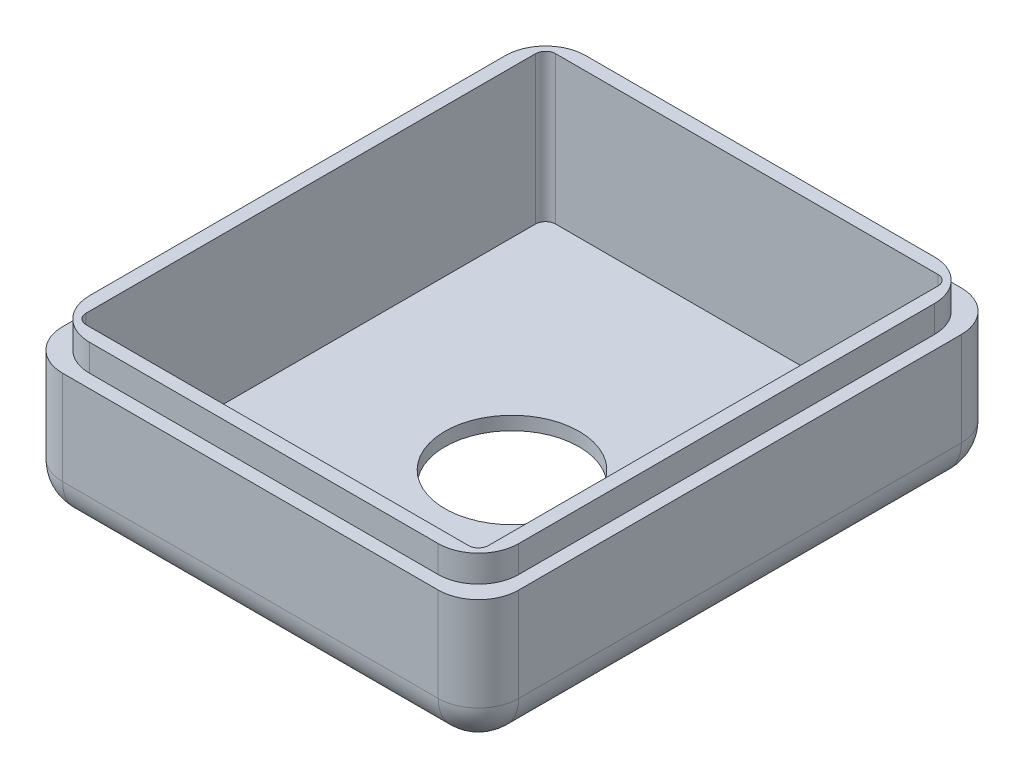
SolidWorks part; units mm, degrees
ref_plane "Piano frontale" through (0, 0, 0) normal (0, 0, 1) x (1, 0, 0)
ref_plane "Piano superiore" through (0, 0, 0) normal (0, 1, 0) x (1, 0, 0)
ref_plane "Piano destro" through (0, 0, 0) normal (1, 0, 0) x (0, 0, -1)
sketch "Schizzo1" plane through (0, 0, 0) normal (0, 1, 0) x (1, 0, 0)
  line L1 (-33.306, 9.8174) -> (0.694, 9.8174)
  line L2 (-33.306, 9.8174) -> (-33.306, -29.1826)
  line L3 (-33.306, -29.1826) -> (0.694, -29.1826)
  line L4 (0.694, 9.8174) -> (0.694, -29.1826)
  dimension "D1" = 39
  dimension "D2" = 34
extrude "Estrusione-Estrusione1" add sketch "Schizzo1" along normal blind 10
sketch "Schizzo4" plane through (0, 10, 0) normal (0, 1, 0) x (1, 0, 0)
  line L0 (-33.306, -29.1826) -> (0.694, -29.1826) construction
  line L1 (-32.306, -28.1826) -> (-0.306, -28.1826)
  line L2 (-32.306, -28.1826) -> (-32.306, 8.8174)
  line L3 (-32.306, 8.8174) -> (-0.306, 8.8174)
  line L4 (-0.306, -28.1826) -> (-0.306, 8.8174)
  line L5 (-33.306, 9.8174) -> (-33.306, -29.1826) construction
  dimension "D1" = 32
  dimension "D2" = 37
  dimension "D3" = 1
  dimension "D4" = 1
extrude "Estrusione-Estrusione2" add sketch "Schizzo4" along normal blind 2
sketch "Schizzo5" plane through (0, 12, 0) normal (0, 1, 0) x (1, 0, 0)
  line L0 (-32.306, -28.1826) -> (-0.306, -28.1826) construction
  line L1 (-31.306, -27.1826) -> (-1.306, -27.1826)
  line L2 (-31.306, -27.1826) -> (-31.306, 7.8174)
  line L3 (-31.306, 7.8174) -> (-1.306, 7.8174)
  line L4 (-1.306, -27.1826) -> (-1.306, 7.8174)
  line L5 (-32.306, 8.8174) -> (-32.306, -28.1826) construction
  dimension "D1" = 1
  dimension "D2" = 1
  dimension "D3" = 35
  dimension "D4" = 30
extrude "Taglio-Estrusione2" cut sketch "Schizzo5" against normal blind 11
fillet "Raccordo1" radius 3 12 edges at (-33.306, 5, 29.1826) (0.694, 5, 29.1826) (-33.306, 5, -9.8174) (0.694, 5, -9.8174) (-0.306, 11, -8.8174) (-0.306, 11, 28.1826) (-32.306, 11, 28.1826) (-32.306, 11, -8.8174) (-16.306, 0, 29.1826) (0.694, 0, 9.6826) (-16.306, 0, -9.8174) (-33.306, 0, 9.6826)
fillet "Raccordo2" radius 0.75 4 edges at (-31.306, 6.5, -7.8174) (-1.306, 6.5, -7.8174) (-1.306, 6.5, 27.1826) (-31.306, 6.5, 27.1826)
sketch "Schizzo6" plane through (0, 0, 0) normal (0, -1, 0) x (1, 0, 0)
  line L2 (-30.306, 26.1826) -> (-30.306, -6.8174) construction
  line L4 (-30.306, -6.8174) -> (-2.306, -6.8174) construction
  circle A0 centre (-16.306, 9.6826) radius 5
  dimension "D1" = 10
  dimension "D2" = 14
  dimension "D3" = 16.5
extrude "Taglio-Estrusione3" cut sketch "Schizzo6" against normal up to next
